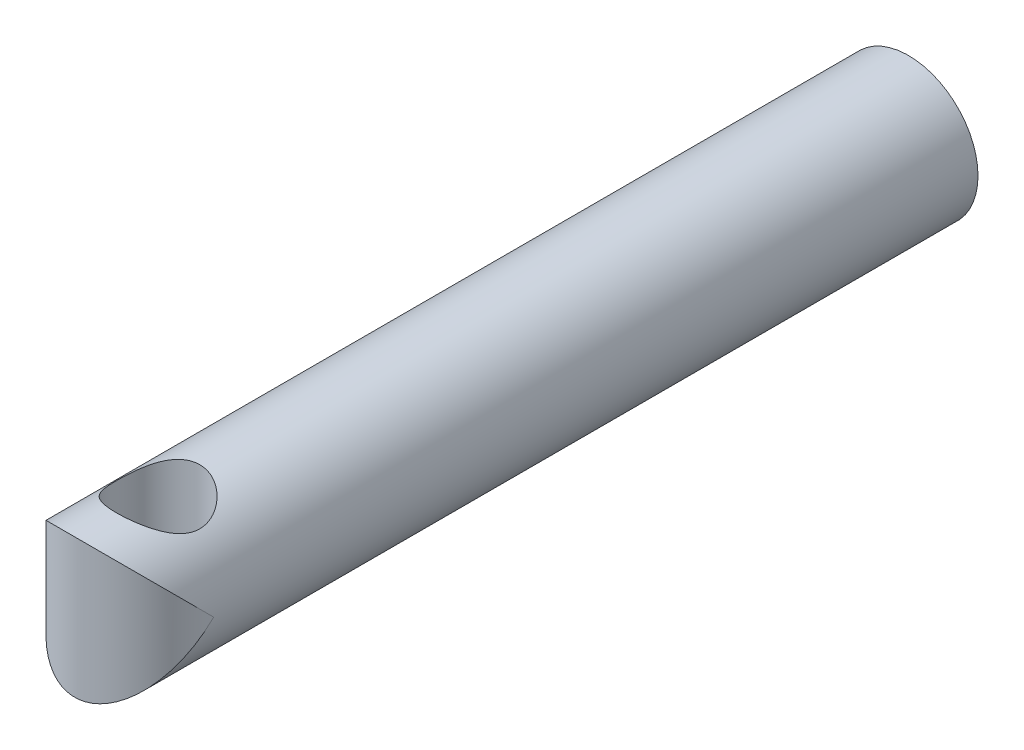
SolidWorks part; units mm, degrees
ref_plane "Front Plane" through (0, 0, 0) normal (0, 0, 1) x (1, 0, 0)
ref_plane "Top Plane" through (0, 0, 0) normal (0, 1, 0) x (1, 0, 0)
ref_plane "Right Plane" through (0, 0, 0) normal (1, 0, 0) x (0, 0, -1)
sketch "Sketch1" plane through (0, 0, 0) normal (0, 0, 1) x (1, 0, 0)
  circle A0 centre (0, 0) radius 2.5
  dimension "D1" = 5
extrude "Boss-Extrude1" add sketch "Sketch1" along normal blind 30
sketch "Sketch2" plane through (0, 0, 0) normal (0, 1, 0) x (1, 0, 0)
  line L0 (-2.5, -30) -> (2.5, -30) construction
  line L1 (0, -30) -> (0, -27) construction
  line L3 (-2.5, -24) -> (2.5, -24)
  line L4 (-2.5, -24) -> (-2.5, -30)
  line L5 (-2.5, -30) -> (2.5, -30)
  line L6 (2.5, -24) -> (2.5, -30)
  line L7 (-2.5, -24) -> (2.5, -30) construction
  line L8 (-2.5, -30) -> (2.5, -24) construction
  circle A0 centre (0, -27) radius 1.5
  arc A1 (-2.5, -27.5) -> (2.5, -27.5) centre (0, -27.5) ccw
  dimension "D2" = 3
  dimension "D1" = 3
extrude "Cut-Extrude1" cut sketch "Sketch2" against normal through all and the other way through all contours A0 | A1 L4 L5 | A1 L5 L6
sketch "Sketch3" plane through (0, 0, 0) normal (0, 1, 0) x (1, 0, 0)
  line L0 (-2.5, 0) -> (2.5, -6)
  line L1 (2.5, -27.5) -> (2.5, 0) construction
  line L2 (2.5, -6) -> (-2.5, -6)
  line L3 (-2.5, 0) -> (-2.5, -27.5) construction
  line L4 (-2.5, -6) -> (-2.5, 0)
  line L5 (2.5, -6) -> (2.5, 0)
  line L6 (2.5, 0) -> (-2.5, 0)
  dimension "D1" = 6
extrude "Cut-Extrude2" [suppressed] cut sketch "Sketch3" against normal through all and the other way through all contours L5 L6 L0
